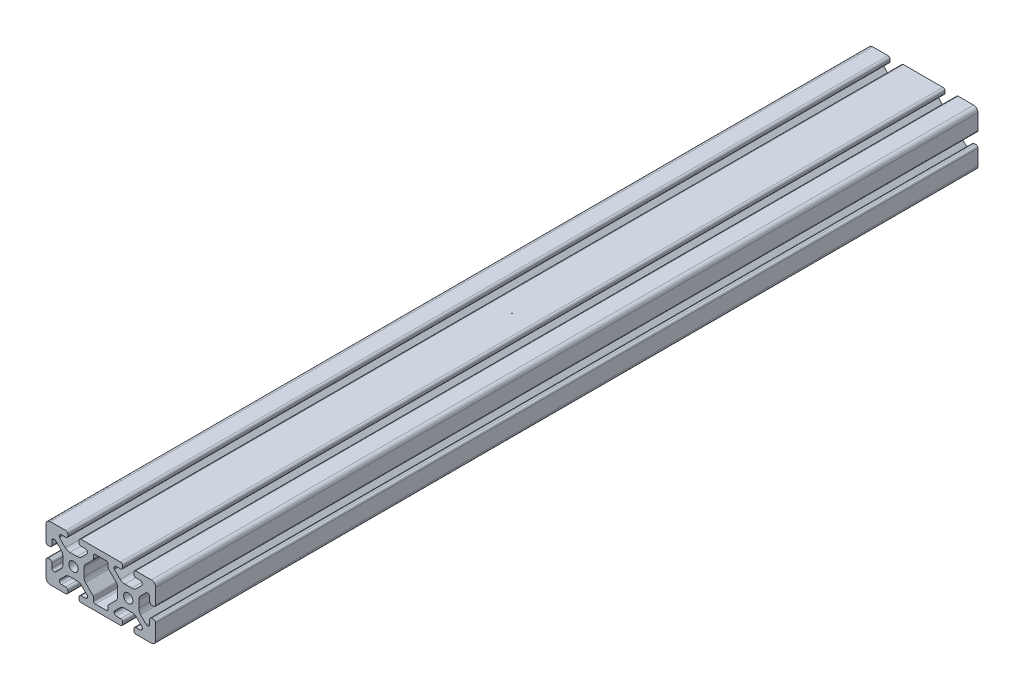
SolidWorks part; units mm, degrees
material "6061 Alloy"
ref_plane "Front Plane" through (0, 0, 0) normal (0, 0, 1) x (1, 0, 0)
ref_plane "Top Plane" through (0, 0, 0) normal (0, 1, 0) x (1, 0, 0)
ref_plane "Right Plane" through (0, 0, 0) normal (1, 0, 0) x (0, 0, -1)
sketch "Sketch1" plane through (0, 0, 0) normal (0, 0, 1) x (1, 0, 0)
  line L0 (-14.3719, 20) -> (14.3719, 20)
  line L1 (-15.94, 17.1729) -> (-15.94, 18.3529)
  line L2 (-11.285, 15.68) -> (-14.37, 15.68)
  line L3 (-9.715, 13.6545) -> (-9.715, 14.11)
  line L4 (4.0718, 15.68) -> (-4.0718, 15.68)
  line L5 (-5.3418, 14.41) -> (-5.3418, 12.1296)
  line L6 (-5.7137, 11.2316) -> (-10.5988, 6.3465)
  line L7 (-12.2841, 3.2591) -> (-12.2841, -2.725)
  line L8 (5.991, -20) -> (-1.7801, -20)
  line L9 (0, 20) -> (0, -25.1394) construction
  line L10 (-4.0718, -15.68) -> (4.0718, -15.68)
  line L11 (-5.3418, -12.1296) -> (-5.3418, -14.41)
  line L12 (-11.2012, -5.7441) -> (-5.7137, -11.2316)
  line L13 (-42.275, 0) -> (43.1806, 0) construction
  line L14 (-9.9376, 13.1171) -> (-14.0919, 8.9628)
  line L15 (-17.4506, 7.7) -> (-22.5494, 7.7)
  line L16 (-25.9081, 8.9628) -> (-30.0624, 13.1171)
  line L17 (-30.285, 13.6545) -> (-30.285, 14.11)
  line L18 (-28.715, 15.68) -> (-25.63, 15.68)
  line L19 (-24.06, 17.25) -> (-24.06, 18.4312)
  line L20 (-25.5696, 20) -> (-33, 20)
  line L21 (-33, 20) -> (-36.83, 20)
  line L22 (-40, 16.8406) -> (-40, 13.0106)
  line L23 (-40, 13.0106) -> (-40, 5.5825)
  line L24 (-38.3243, 4.06) -> (-37.1443, 4.06)
  line L25 (-35.68, 5.6264) -> (-35.68, 8.7114)
  line L26 (-34.11, 10.2814) -> (-33.6509, 10.2814)
  line L27 (-33.1135, 10.0588) -> (-29.0111, 5.9564)
  line L28 (-27.7159, 2.571) -> (-27.7159, -2.502)
  line L29 (-28.9155, -5.8608) -> (-33.1719, -10.1172)
  line L30 (-33.7093, -10.3398) -> (-34.111, -10.3398)
  line L31 (-35.68, -8.715) -> (-35.68, -5.63)
  line L32 (-37.25, -4.06) -> (-38.43, -4.06)
  line L33 (-40, -5.5696) -> (-40, -13)
  line L34 (-40, -13) -> (-40, -16.83)
  line L35 (-37.0574, -20) -> (-33.2274, -20)
  line L36 (-33.2274, -20) -> (-25.797, -20)
  line L37 (-24.06, -18.4389) -> (-24.06, -17.25)
  line L38 (-25.63, -15.68) -> (-28.715, -15.68)
  line L39 (-30.285, -14.11) -> (-30.285, -13.6545)
  line L40 (-30.0624, -13.1171) -> (-26.3095, -9.3642)
  line L41 (-23.3415, -7.7) -> (-16.6585, -7.7)
  line L42 (-13.6905, -9.3642) -> (-9.9376, -13.1171)
  line L43 (-9.715, -13.6545) -> (-9.715, -14.11)
  line L44 (-11.285, -15.68) -> (-14.37, -15.68)
  line L45 (-15.94, -17.25) -> (-15.94, -18.43)
  line L46 (-14.37, -20) -> (-5.991, -20)
  line L47 (-5.991, -20) -> (-1.7801, -20)
  line L48 (14.37, -20) -> (5.991, -20)
  line L49 (15.94, -17.25) -> (15.94, -18.43)
  line L50 (11.285, -15.68) -> (14.37, -15.68)
  line L51 (9.715, -13.6545) -> (9.715, -14.11)
  line L52 (13.6905, -9.3642) -> (9.9376, -13.1171)
  line L53 (23.3415, -7.7) -> (16.6585, -7.7)
  line L54 (30.0624, -13.1171) -> (26.3095, -9.3642)
  line L55 (30.285, -14.11) -> (30.285, -13.6545)
  line L56 (25.63, -15.68) -> (28.715, -15.68)
  line L57 (24.06, -18.4389) -> (24.06, -17.25)
  line L58 (33.2274, -20) -> (25.797, -20)
  line L59 (37.0574, -20) -> (33.2274, -20)
  line L60 (40, -13) -> (40, -16.83)
  line L61 (40, -5.5696) -> (40, -13)
  line L62 (37.25, -4.06) -> (38.43, -4.06)
  line L63 (35.68, -8.715) -> (35.68, -5.63)
  line L64 (33.7093, -10.3398) -> (34.111, -10.3398)
  line L65 (28.9155, -5.8608) -> (33.1719, -10.1172)
  line L66 (27.7159, 2.571) -> (27.7159, -2.502)
  line L67 (33.1135, 10.0588) -> (29.0111, 5.9564)
  line L68 (34.11, 10.2814) -> (33.6509, 10.2814)
  line L69 (35.68, 5.6264) -> (35.68, 8.7114)
  line L70 (38.3243, 4.06) -> (37.1443, 4.06)
  line L71 (40, 13.0106) -> (40, 5.5825)
  line L72 (40, 16.8406) -> (40, 13.0106)
  line L73 (33, 20) -> (36.83, 20)
  line L74 (25.5696, 20) -> (33, 20)
  line L75 (24.06, 17.25) -> (24.06, 18.4312)
  line L76 (28.715, 15.68) -> (25.63, 15.68)
  line L77 (30.285, 13.6545) -> (30.285, 14.11)
  line L78 (25.9081, 8.9628) -> (30.0624, 13.1171)
  line L79 (17.4506, 7.7) -> (22.5494, 7.7)
  line L80 (9.9376, 13.1171) -> (14.0919, 8.9628)
  line L81 (11.2012, -5.7441) -> (5.7137, -11.2316)
  line L82 (5.3418, -12.1296) -> (5.3418, -14.41)
  line L83 (12.2841, 3.2591) -> (12.2841, -2.725)
  line L84 (5.7137, 11.2316) -> (10.5988, 6.3465)
  line L85 (5.3418, 14.41) -> (5.3418, 12.1296)
  line L86 (9.715, 13.6545) -> (9.715, 14.11)
  line L87 (11.285, 15.68) -> (14.37, 15.68)
  line L88 (15.94, 17.1729) -> (15.94, 18.3529)
  line L89 (-20, 24.8708) -> (-20, -18.43) construction
  line L90 (20, 29.4355) -> (20, -23.1087) construction
  line L91 (-3.0962, 16.9038) -> (-43.6857, -23.6857) construction
  line L92 (-36.2671, 16.2671) -> (-2.7875, -17.2125) construction
  arc A0 (-15.94, 18.3529) -> (-14.3719, 20) centre (-14.3719, 18.43) cw
  circle A1 centre (-20, 0) radius 3.4
  arc A2 (-14.37, 15.68) -> (-15.94, 17.1729) centre (-14.3719, 17.25) cw
  arc A3 (-11.285, 15.68) -> (-9.715, 14.11) centre (-11.285, 14.11) cw
  arc A4 (-9.715, 13.6545) -> (-9.9376, 13.1171) centre (-10.475, 13.6545) cw
  arc A5 (-12.2841, -2.725) -> (-11.2012, -5.7441) centre (-7.5341, -2.725) ccw
  arc A6 (-4.0718, 15.68) -> (-5.3418, 14.41) centre (-4.0718, 14.41) ccw
  arc A7 (-5.7137, 11.2316) -> (-5.3418, 12.1296) centre (-6.6118, 12.1296) ccw
  arc A8 (-10.5988, 6.3465) -> (-12.2841, 3.2591) centre (-7.5685, 2.6887) ccw
  arc A9 (-5.3418, -14.41) -> (-4.0718, -15.68) centre (-4.0718, -14.41) ccw
  arc A10 (-5.3418, -12.1296) -> (-5.7137, -11.2316) centre (-6.6118, -12.1296) ccw
  arc A11 (-17.4506, 7.7) -> (-14.0919, 8.9628) centre (-17.3191, 12.4482) ccw
  arc A12 (-25.9081, 8.9628) -> (-22.5494, 7.7) centre (-22.6809, 12.4482) ccw
  arc A13 (-30.285, 13.6545) -> (-30.0624, 13.1171) centre (-29.525, 13.6545) ccw
  arc A14 (-28.715, 15.68) -> (-30.285, 14.11) centre (-28.715, 14.11) ccw
  arc A15 (-25.63, 15.68) -> (-24.06, 17.25) centre (-25.63, 17.25) ccw
  arc A16 (-24.06, 18.4312) -> (-25.5696, 20) centre (-25.63, 18.4312) ccw
  arc A17 (-36.83, 20) -> (-40, 16.8406) centre (-36.83, 16.83) ccw
  arc A18 (-40, 5.5825) -> (-38.3243, 4.06) centre (-38.4306, 5.6264) ccw
  arc A19 (-37.1443, 4.06) -> (-35.68, 5.6264) centre (-37.25, 5.6264) ccw
  arc A20 (-34.11, 10.2814) -> (-35.68, 8.7114) centre (-34.11, 8.7114) ccw
  arc A21 (-33.1135, 10.0588) -> (-33.6509, 10.2814) centre (-33.6509, 9.5214) ccw
  arc A22 (-27.7159, 2.571) -> (-29.0111, 5.9564) centre (-32.4643, 2.6948) ccw
  arc A23 (-28.9155, -5.8608) -> (-27.7159, -2.502) centre (-32.4617, -2.7006) ccw
  arc A24 (-33.7093, -10.3398) -> (-33.1719, -10.1172) centre (-33.7093, -9.5798) ccw
  arc A25 (-35.68, -8.715) -> (-34.111, -10.3398) centre (-34.111, -8.7698) ccw
  arc A26 (-35.68, -5.63) -> (-37.25, -4.06) centre (-37.25, -5.63) ccw
  arc A27 (-38.43, -4.06) -> (-40, -5.5696) centre (-38.4312, -5.63) ccw
  arc A28 (-40, -16.83) -> (-37.0574, -20) centre (-36.83, -16.8382) ccw
  arc A29 (-25.797, -20) -> (-24.06, -18.4389) centre (-25.63, -18.4389) ccw
  arc A30 (-24.06, -17.25) -> (-25.63, -15.68) centre (-25.63, -17.25) ccw
  arc A31 (-30.285, -14.11) -> (-28.715, -15.68) centre (-28.715, -14.11) ccw
  arc A32 (-30.0624, -13.1171) -> (-30.285, -13.6545) centre (-29.525, -13.6545) ccw
  arc A33 (-23.3415, -7.7) -> (-26.3095, -9.3642) centre (-22.6565, -12.4003) ccw
  arc A34 (-13.6905, -9.3642) -> (-16.6585, -7.7) centre (-17.3435, -12.4003) ccw
  arc A35 (-9.715, -13.6545) -> (-9.9376, -13.1171) centre (-10.475, -13.6545) ccw
  arc A36 (-11.285, -15.68) -> (-9.715, -14.11) centre (-11.285, -14.11) ccw
  arc A37 (-14.37, -15.68) -> (-15.94, -17.25) centre (-14.37, -17.25) ccw
  arc A38 (-15.94, -18.43) -> (-14.37, -20) centre (-14.37, -18.43) ccw
  arc A39 (15.94, -18.43) -> (14.37, -20) centre (14.37, -18.43) cw
  arc A40 (14.37, -15.68) -> (15.94, -17.25) centre (14.37, -17.25) cw
  arc A41 (11.285, -15.68) -> (9.715, -14.11) centre (11.285, -14.11) cw
  arc A42 (9.715, -13.6545) -> (9.9376, -13.1171) centre (10.475, -13.6545) cw
  arc A43 (13.6905, -9.3642) -> (16.6585, -7.7) centre (17.3435, -12.4003) cw
  arc A44 (23.3415, -7.7) -> (26.3095, -9.3642) centre (22.6565, -12.4003) cw
  arc A45 (30.0624, -13.1171) -> (30.285, -13.6545) centre (29.525, -13.6545) cw
  arc A46 (30.285, -14.11) -> (28.715, -15.68) centre (28.715, -14.11) cw
  arc A47 (24.06, -17.25) -> (25.63, -15.68) centre (25.63, -17.25) cw
  arc A48 (25.797, -20) -> (24.06, -18.4389) centre (25.63, -18.4389) cw
  arc A49 (40, -16.83) -> (37.0574, -20) centre (36.83, -16.8382) cw
  arc A50 (38.43, -4.06) -> (40, -5.5696) centre (38.4312, -5.63) cw
  arc A51 (35.68, -5.63) -> (37.25, -4.06) centre (37.25, -5.63) cw
  arc A52 (35.68, -8.715) -> (34.111, -10.3398) centre (34.111, -8.7698) cw
  arc A53 (33.7093, -10.3398) -> (33.1719, -10.1172) centre (33.7093, -9.5798) cw
  arc A54 (28.9155, -5.8608) -> (27.7159, -2.502) centre (32.4617, -2.7006) cw
  arc A55 (27.7159, 2.571) -> (29.0111, 5.9564) centre (32.4643, 2.6948) cw
  arc A56 (33.1135, 10.0588) -> (33.6509, 10.2814) centre (33.6509, 9.5214) cw
  arc A57 (34.11, 10.2814) -> (35.68, 8.7114) centre (34.11, 8.7114) cw
  arc A58 (37.1443, 4.06) -> (35.68, 5.6264) centre (37.25, 5.6264) cw
  arc A59 (40, 5.5825) -> (38.3243, 4.06) centre (38.4306, 5.6264) cw
  arc A60 (36.83, 20) -> (40, 16.8406) centre (36.83, 16.83) cw
  arc A61 (24.06, 18.4312) -> (25.5696, 20) centre (25.63, 18.4312) cw
  arc A62 (25.63, 15.68) -> (24.06, 17.25) centre (25.63, 17.25) cw
  arc A63 (28.715, 15.68) -> (30.285, 14.11) centre (28.715, 14.11) cw
  arc A64 (30.285, 13.6545) -> (30.0624, 13.1171) centre (29.525, 13.6545) cw
  arc A65 (25.9081, 8.9628) -> (22.5494, 7.7) centre (22.6809, 12.4482) cw
  arc A66 (17.4506, 7.7) -> (14.0919, 8.9628) centre (17.3191, 12.4482) cw
  arc A67 (5.3418, -12.1296) -> (5.7137, -11.2316) centre (6.6118, -12.1296) cw
  arc A68 (5.3418, -14.41) -> (4.0718, -15.68) centre (4.0718, -14.41) cw
  arc A69 (10.5988, 6.3465) -> (12.2841, 3.2591) centre (7.5685, 2.6887) cw
  arc A70 (5.7137, 11.2316) -> (5.3418, 12.1296) centre (6.6118, 12.1296) cw
  arc A71 (4.0718, 15.68) -> (5.3418, 14.41) centre (4.0718, 14.41) cw
  arc A72 (12.2841, -2.725) -> (11.2012, -5.7441) centre (7.5341, -2.725) cw
  arc A73 (9.715, 13.6545) -> (9.9376, 13.1171) centre (10.475, 13.6545) ccw
  arc A74 (11.285, 15.68) -> (9.715, 14.11) centre (11.285, 14.11) ccw
  arc A75 (14.37, 15.68) -> (15.94, 17.1729) centre (14.3719, 17.25) ccw
  circle A76 centre (20, 0) radius 3.4
  arc A77 (15.94, 18.3529) -> (14.3719, 20) centre (14.3719, 18.43) ccw
  dimension "D4" = 6.8
  dimension "D1" = 80
  dimension "D2" = 40
  dimension "D3" = 20
  dimension "D5" = 8.12
  dimension "D6" = 4.32
  dimension "D7" = 20.57
  dimension "D8" = 4.32
  dimension "D9" = 8.12
  dimension "D10" = 12.3
  dimension "D11" = 4.32
  dimension "D12" = 4.32
  dimension "D13" = 4.32
extrude "Extrude1" add sketch "Sketch1" against normal blind 600
sketch "Sketch2" plane through (0, 20, 0) normal (0, 1, 0) x (1, 0, 0)
  line L0 (0, 600) -> (0, 0) construction
  line L1 (14.3719, 600) -> (-14.3719, 600) construction
  circle A0 centre (0, 300) radius 0.25
  dimension "D1" = 0.5
extrude "Skinny Side" cut sketch "Sketch2" against normal blind 1
sketch "Sketch3" plane through (-40, 0, 0) normal (-1, 0, 0) x (0, 0, 1)
  line L0 (-600, 0.0345) -> (0, 0) construction
  line L1 (-600, 2.571) -> (-600, -2.502) construction
  circle A0 centre (-300, 0.0172) radius 0.25
  dimension "D1" = 0.5
extrude "Cut-Extrude3" cut sketch "Sketch3" against normal through all
